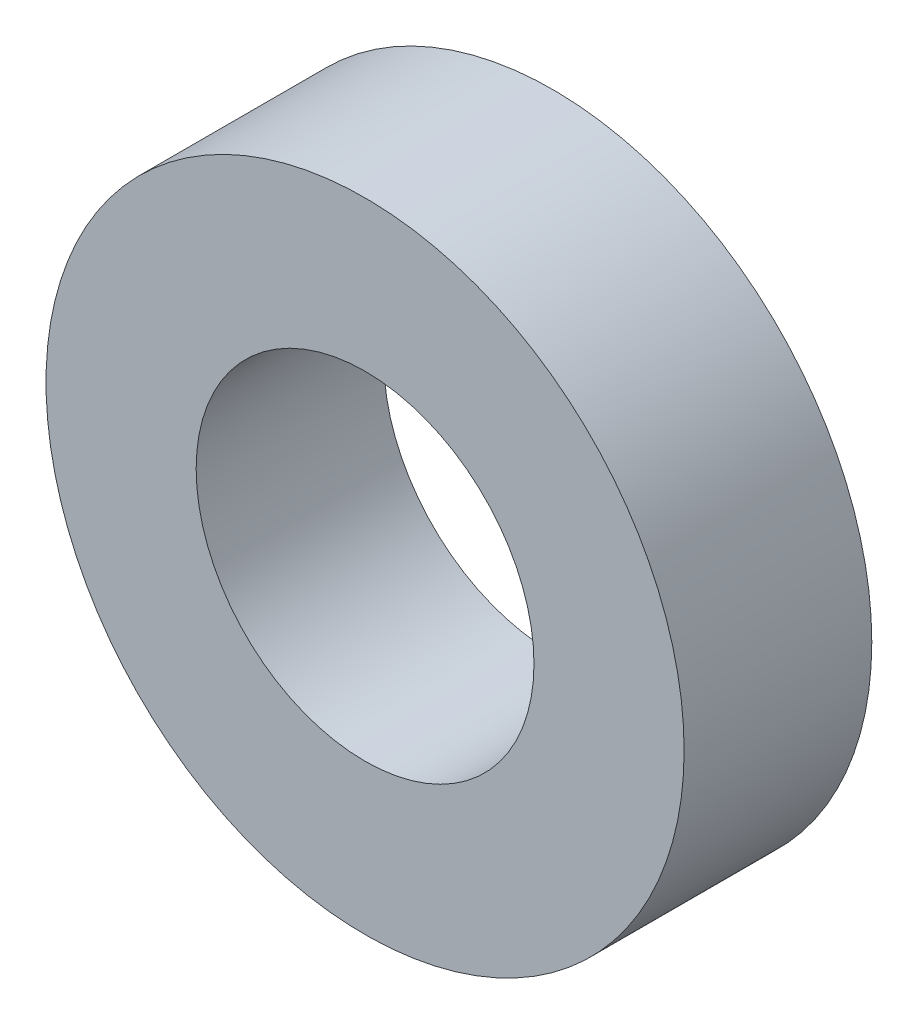
SolidWorks part; units mm, degrees
ref_plane "Front Plane" through (0, 0, 0) normal (0, 0, 1) x (1, 0, 0)
ref_plane "Top Plane" through (0, 0, 0) normal (0, 1, 0) x (1, 0, 0)
ref_plane "Right Plane" through (0, 0, 0) normal (1, 0, 0) x (0, 0, -1)
sketch "Sketch1" plane through (0, 0, 0) normal (0, 0, 1) x (1, 0, 0)
  circle A0 centre (0, 0) radius 4.5
  circle A1 centre (0, 0) radius 8.5
  dimension "D1" = 9
  dimension "D2" = 4
extrude "Boss-Extrude1" add sketch "Sketch1" along normal blind 5
